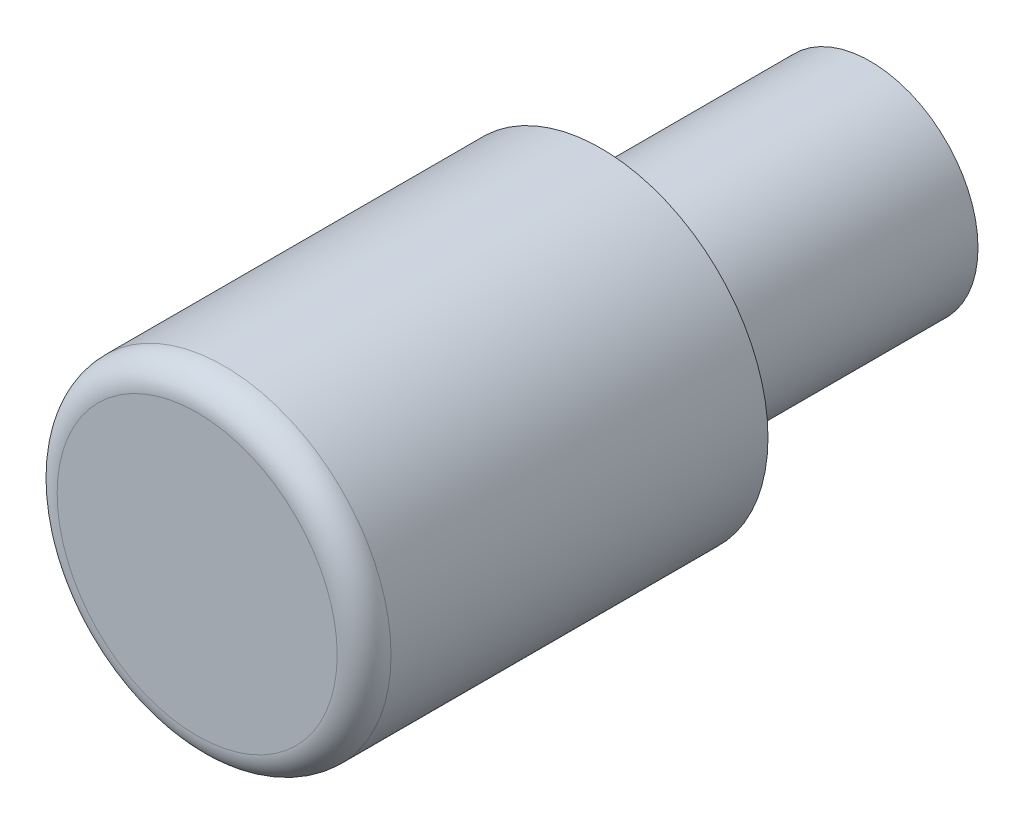
SolidWorks part; units mm, degrees
material "Chrome Stainless Steel"
ref_plane "Front Plane" through (0, 0, 0) normal (0, 0, 1) x (1, 0, 0)
ref_plane "Top Plane" through (0, 0, 0) normal (0, 1, 0) x (1, 0, 0)
ref_plane "Right Plane" through (0, 0, 0) normal (1, 0, 0) x (0, 0, -1)
sketch "Sketch1" plane through (0, 0, 0) normal (0, 0, 1) x (1, 0, 0)
  circle A0 centre (0, 0) radius 1.5748
extrude "Boss-Extrude1" add sketch "Sketch1" along normal blind 3.81
sketch "Sketch2" plane through (0, 0, 0) normal (0, 0, -1) x (-1, 0, 0)
  circle A0 centre (0, 0) radius 1.016
  dimension "D1" = 2.032
extrude "Boss-Extrude2" add sketch "Sketch2" along normal blind 2.54
fillet "Fillet1" radius 0.254 1 edges at (1.5748, 0, 3.81)
